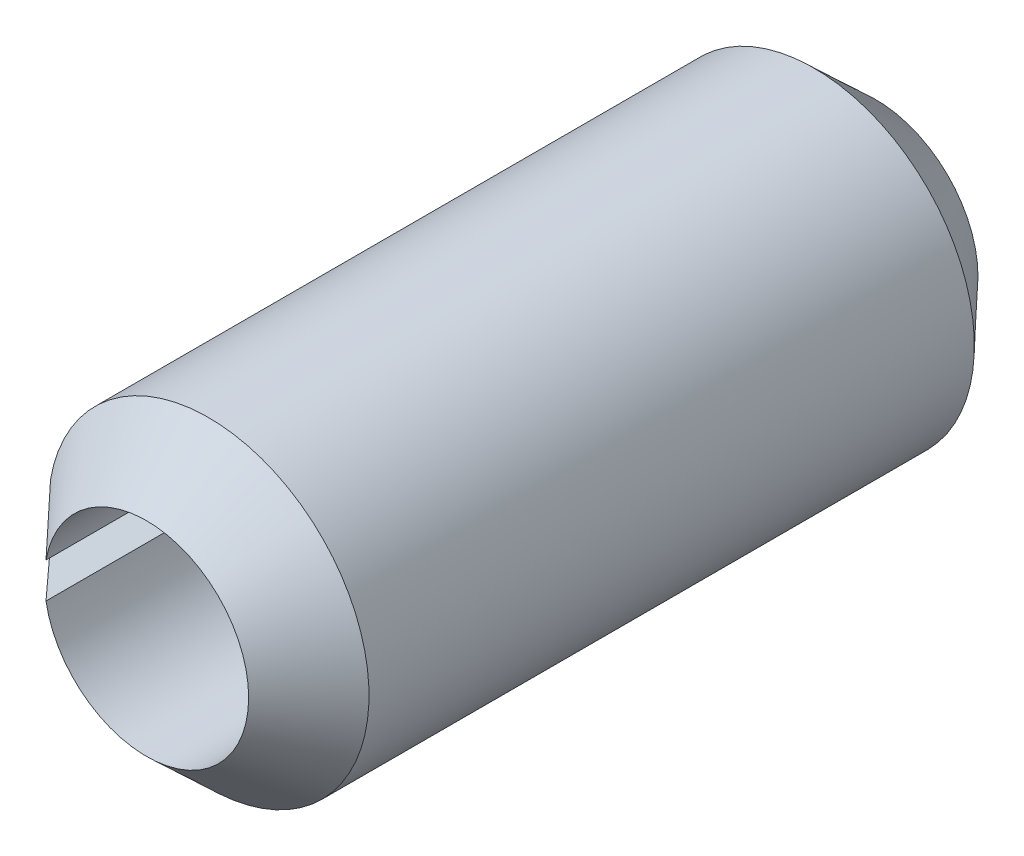
SolidWorks part; units mm, degrees
ref_plane "Front Plane" through (0, 0, 0) normal (0, 0, 1) x (1, 0, 0)
ref_plane "Top Plane" through (0, 0, 0) normal (0, 1, 0) x (1, 0, 0)
ref_plane "Right Plane" through (0, 0, 0) normal (1, 0, 0) x (0, 0, -1)
sketch "Sketch1" plane through (0, 0, 0) normal (0, 0, 1) x (1, 0, 0)
  line L0 (1.4, 0) -> (2.2, 0) construction
  line L1 (-2.1666, 0.382) -> (-1.3787, 0.2431)
  line L2 (-1.3787, -0.2431) -> (-2.1666, -0.382)
  arc A0 (-2.1666, -0.382) -> (-2.1666, 0.382) centre (0, 0) ccw
  arc A1 (-1.3787, -0.2431) -> (-1.3787, 0.2431) centre (0, 0) ccw
  dimension "OD" = 4.4
  dimension "Wall thickness" = 0.8
  dimension "D3" = 20
extrude "Extrude1" add sketch "Sketch1" along normal mid plane 10
sketch "Sketch2" plane through (0, 0, 0) normal (1, 0, 0) x (0, 0, -1)
  line L0 (0, -2.2) -> (0, 2.2) construction
  line L1 (5, 0) -> (-5, 0) construction
  line L2 (5, -1.4) -> (5, 1.4) construction
  line L3 (5, 2.2) -> (-5, 2.2) construction
  line L4 (5, 2.2) -> (5, 1.4)
  line L5 (5, 1.4) -> (4.15, 2.2)
  line L6 (4.15, 2.2) -> (5, 2.2)
  line L7 (5, -2.2) -> (5, 2.2) construction
  line L8 (-4.15, 2.2) -> (-5, 2.2)
  line L9 (-5, 1.4) -> (-4.15, 2.2)
  line L10 (-5, 2.2) -> (-5, 1.4)
  line L11 (4.15, -2.2) -> (5, -2.2) construction
  line L12 (5, -1.4) -> (4.15, -2.2) construction
  line L13 (5, -2.2) -> (5, -1.4) construction
  dimension "B" = 2.8
  dimension "Chamfer max" = 0.85
revolve "Cut-Revolve1" cut sketch "Sketch2" angle 360 about L1
sketch "Sketch3" plane through (0, 0, 0) normal (0, 0, 1) x (1, 0, 0)
  line L0 (1.4, 0) -> (2.2, 0) construction
  line L1 (1.4, 0) -> (2.2, 0)
  circle A0 centre (0, 0) radius 2.2
  circle A1 centre (0, 0) radius 1.4
  arc A2 (-2.1666, -0.382) -> (-2.1666, 0.382) centre (0, 0) ccw construction
  arc A3 (-1.3787, -0.2431) -> (-1.3787, 0.2431) centre (0, 0) ccw construction
